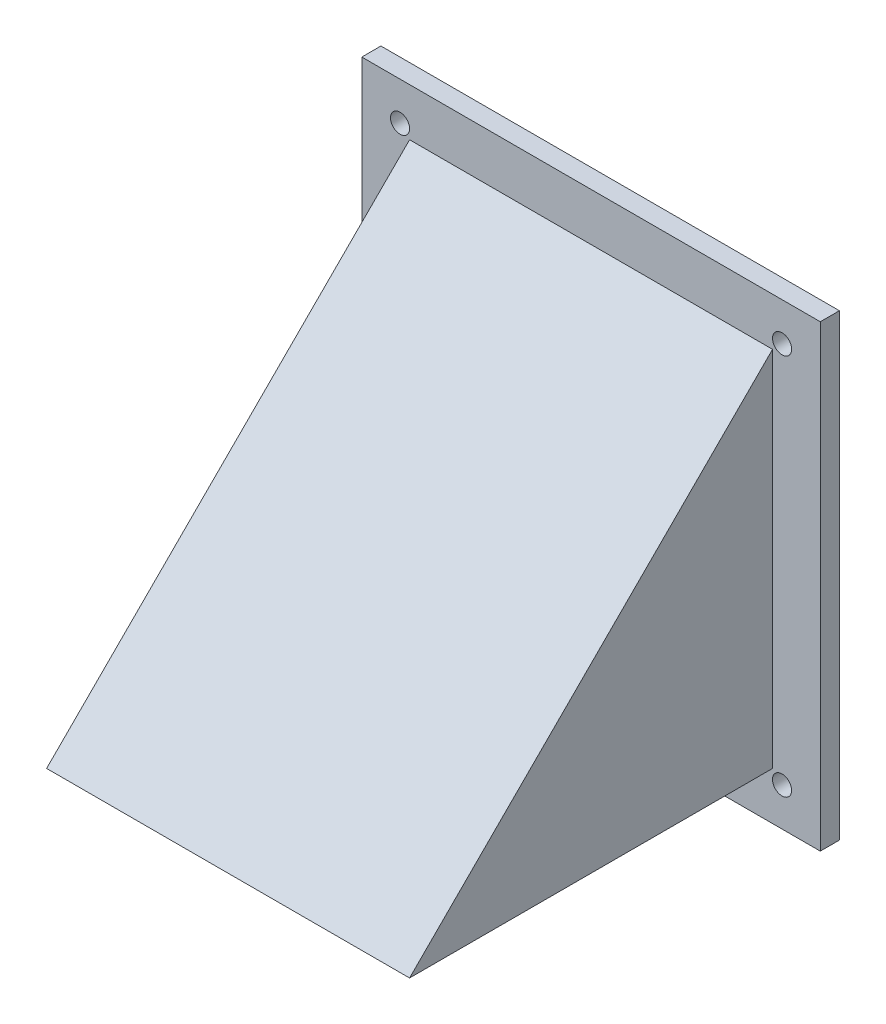
SolidWorks part; units mm, degrees
ref_plane "Front Plane" through (0, 0, 0) normal (0, 0, 1) x (1, 0, 0)
ref_plane "Top Plane" through (0, 0, 0) normal (0, 1, 0) x (1, 0, 0)
ref_plane "Right Plane" through (0, 0, 0) normal (1, 0, 0) x (0, 0, -1)
sketch "Sketch2" plane through (0, 0, 0) normal (0, 0, 1) x (1, 0, 0)
  line L1 (0, 0) -> (120, 0)
  line L2 (0, 0) -> (0, -120)
  line L3 (0, -120) -> (120, -120)
  line L4 (120, 0) -> (120, -120)
  line L5 (16.25, -16.25) -> (103.75, -16.25)
  line L6 (16.25, -16.25) -> (16.25, -103.75)
  line L7 (16.25, -103.75) -> (103.75, -103.75)
  line L8 (103.75, -16.25) -> (103.75, -103.75)
  circle A0 centre (10, -10) radius 2.5
  circle A1 centre (110, -10) radius 2.5
  circle A2 centre (9.989, -110) radius 2.5
  circle A3 centre (109.989, -110) radius 2.5
  dimension "D7" = 5
  dimension "D8" = 5
  dimension "D9" = 5
  dimension "D10" = 5
  dimension "D13" = 10
  dimension "D1" = 120
  dimension "D2" = 120
  dimension "D3" = 100
  dimension "D4" = 100
  dimension "D5" = 100
  dimension "D6" = 100
  dimension "D11" = 10
  dimension "D12" = 10
  dimension "D14" = 87.5
  dimension "D15" = 87.5
  dimension "D16" = 16.25
  dimension "D17" = 16.25
extrude "Boss-Extrude1" add sketch "Sketch2" along normal blind 5
sketch "Sketch3" plane through (0, 0, 5) normal (0, 0, 1) x (1, 0, 0)
  line L8 (12.5, -12.5) -> (12.5, -107.5)
  line L9 (12.5, -107.5) -> (107.5, -107.5)
  line L10 (107.5, -107.5) -> (107.5, -12.5)
  line L11 (107.5, -12.5) -> (12.5, -12.5)
  line L12 (12.5, -12.5) -> (12.5, -107.5)
  line L13 (12.5, -107.5) -> (107.5, -107.5)
  line L14 (107.5, -107.5) -> (107.5, -12.5)
  line L15 (107.5, -12.5) -> (12.5, -12.5)
  dimension "D1" = 12.5
extrude "Boss-Extrude2" add sketch "Sketch3" along normal blind 95 contours L12 L13 L14 L15
sketch "Sketch4" plane through (107.5, 0, 0) normal (1, 0, 0) x (0, 0, -1)
  line L0 (-5, -12.5) -> (-100, -107.5)
  line L1 (-100, -107.5) -> (-100, -12.5)
  line L2 (-100, -12.5) -> (-5, -12.5)
extrude "Cut-Extrude1" cut sketch "Sketch4" against normal blind 95
sketch "Sketch5" plane through (0, -107.5, 0) normal (0, -1, 0) x (1, 0, 0)
  line L0 (12.5, 100) -> (107.5, 100) construction
  line L1 (16.25, 96.25) -> (103.75, 96.25)
  line L2 (16.25, 96.25) -> (16.25, 8.75)
  line L3 (16.25, 8.75) -> (103.75, 8.75)
  line L4 (103.75, 96.25) -> (103.75, 8.75)
  line L5 (12.5, 100) -> (12.5, 5) construction
  dimension "D1" = 87.5
  dimension "D2" = 87.5
  dimension "D3" = 3.75
  dimension "D4" = 3.75
extrude "Cut-Extrude4" cut sketch "Sketch5" against normal offset from surface (0.2145 mm away) 2.5
sketch "Sketch9" plane through (0, 0, 5) normal (0, 0, -1) x (-1, 0, 0)
  line L1 (-103.75, -19.7855) -> (-16.25, -19.7855)
  line L2 (-103.75, -19.7855) -> (-103.75, -103.75)
  line L3 (-103.75, -103.75) -> (-16.25, -103.75)
  line L4 (-16.25, -19.7855) -> (-16.25, -103.75)
extrude "Cut-Extrude5" cut sketch "Sketch9" against normal up to next
sketch "Sketch10" plane through (103.75, 0, 0) normal (-1, 0, 0) x (0, 0, 1)
  line L0 (8.75, -19.7855) -> (5, -19.7855)
  line L1 (5, -19.7855) -> (5, -16.25)
  line L2 (5, -16.25) -> (8.75, -19.7855)
extrude "Cut-Extrude7" cut sketch "Sketch10" along normal blind 87.5
